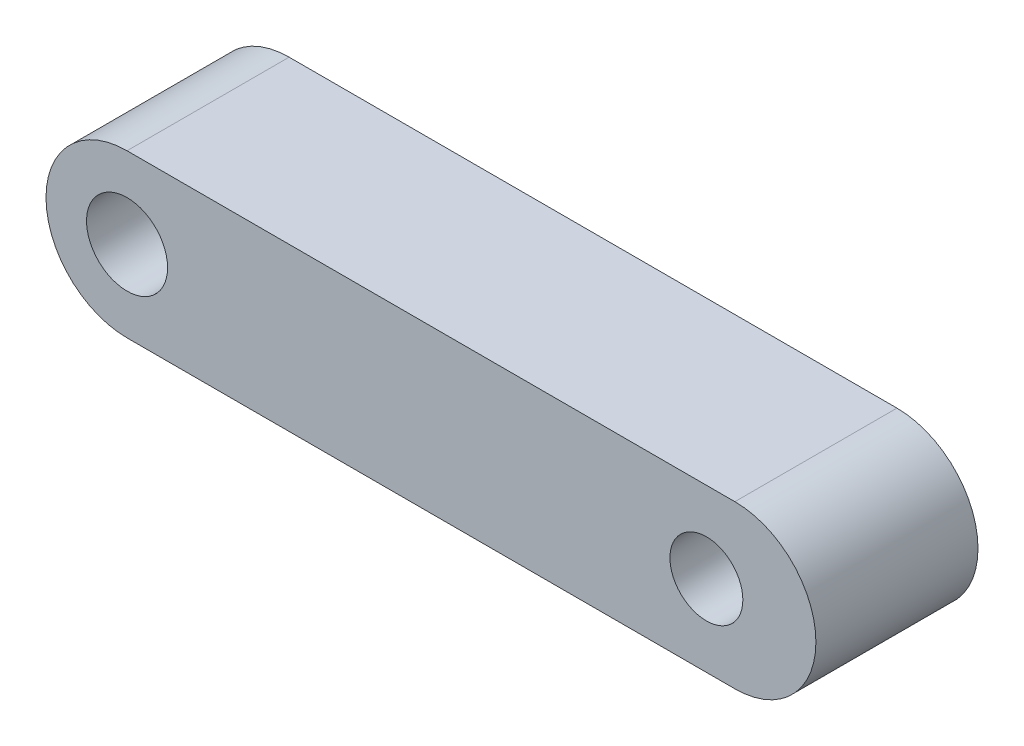
SolidWorks part; units mm, degrees
ref_plane "Alzado" through (0, 0, 0) normal (0, 0, 1) x (1, 0, 0)
ref_plane "Planta" through (0, 0, 0) normal (0, 1, 0) x (1, 0, 0)
ref_plane "Vista lateral" through (0, 0, 0) normal (1, 0, 0) x (0, 0, -1)
sketch "Croquis1" plane through (0, 0, 0) normal (0, 0, 1) x (1, 0, 0)
  line L0 (-15.1361, 0) -> (-0.1361, 0) construction
  line L1 (-15.1361, 2) -> (-0.1361, 2)
  line L2 (-15.1361, -2) -> (-0.1361, -2)
  arc A0 (-15.1361, 2) -> (-15.1361, -2) centre (-15.1361, 0) ccw
  arc A1 (-0.1361, -2) -> (-0.1361, 2) centre (-0.1361, 0) ccw
  point P3 (-7.6361, 0)
  dimension "D2" = 2
  dimension "D1" = 15
extrude "Saliente-Extruir1" add sketch "Croquis1" along normal blind 4
sketch "Croquis2" plane through (0, 0, 4) normal (0, 0, 1) x (1, 0, 0)
  circle A0 centre (-15.1361, 0) radius 1
  circle A1 centre (-0.8391, 0) radius 0.9
  dimension "D1" = 2
  dimension "D2" = 1.8
extrude "Cortar-Extruir1" cut sketch "Croquis2" against normal through all
